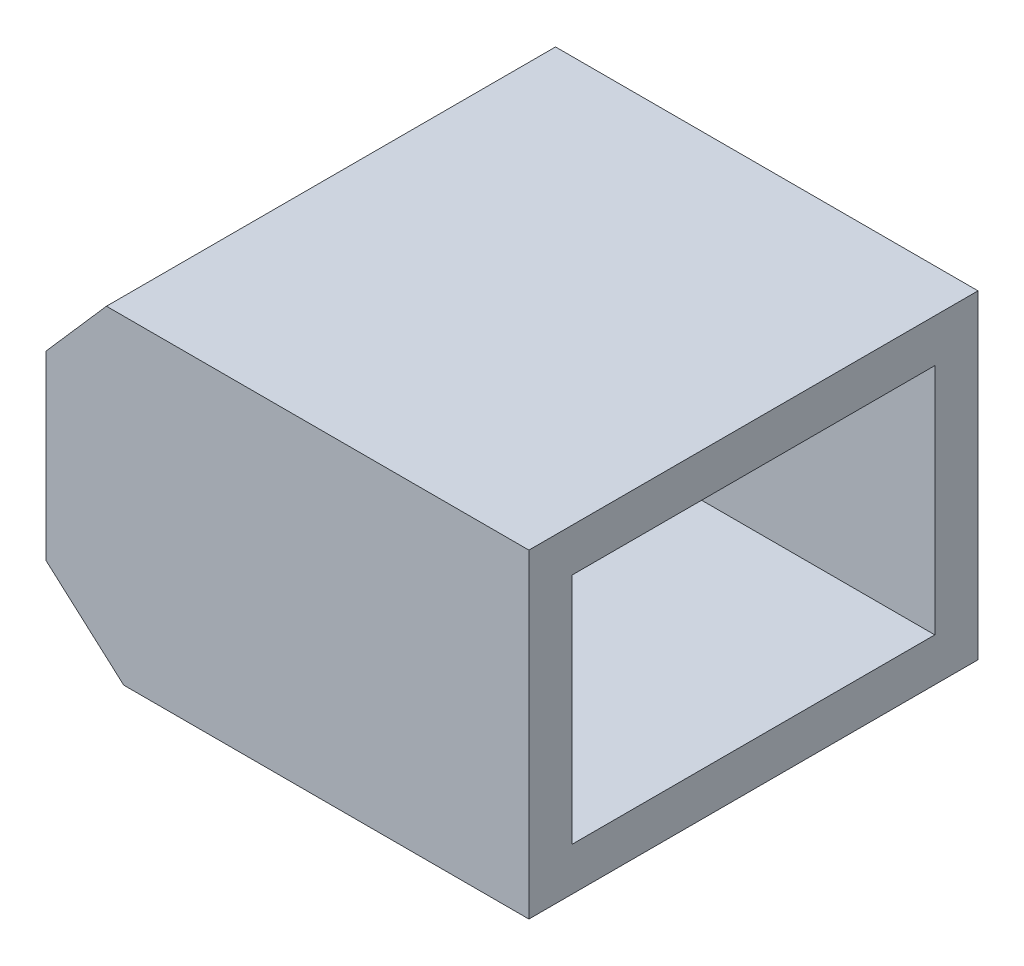
SolidWorks part; units mm, degrees
ref_plane "前视基准面" through (0, 0, 0) normal (0, 0, 1) x (1, 0, 0)
ref_plane "上视基准面" through (0, 0, 0) normal (0, 1, 0) x (1, 0, 0)
ref_plane "右视基准面" through (0, 0, 0) normal (1, 0, 0) x (0, 0, -1)
other "Configuration Table"
sketch "草图1" plane through (0, 0, 0) normal (0, 0, 1) x (1, 0, 0)
  line L0 (0.9152, 0) -> (-48, 0)
  line L1 (-48, 0) -> (-55, -8)
  line L2 (-55, -8) -> (-55, -29)
  line L3 (-55, -29) -> (-46, -37)
  line L4 (-46, -37) -> (0.9152, -37)
  line L5 (0.9152, -37) -> (0.9152, 0)
  dimension "x0" = 0.9152
  dimension "x1" = 48
  dimension "x2" = 55
  dimension "x4" = 46
  dimension "y2" = 8
  dimension "y3" = 29
  dimension "y4" = 37
extrude "Closing_lip_profile" add sketch "草图1" along normal blind 52
shell "抽壳1" thickness 5
